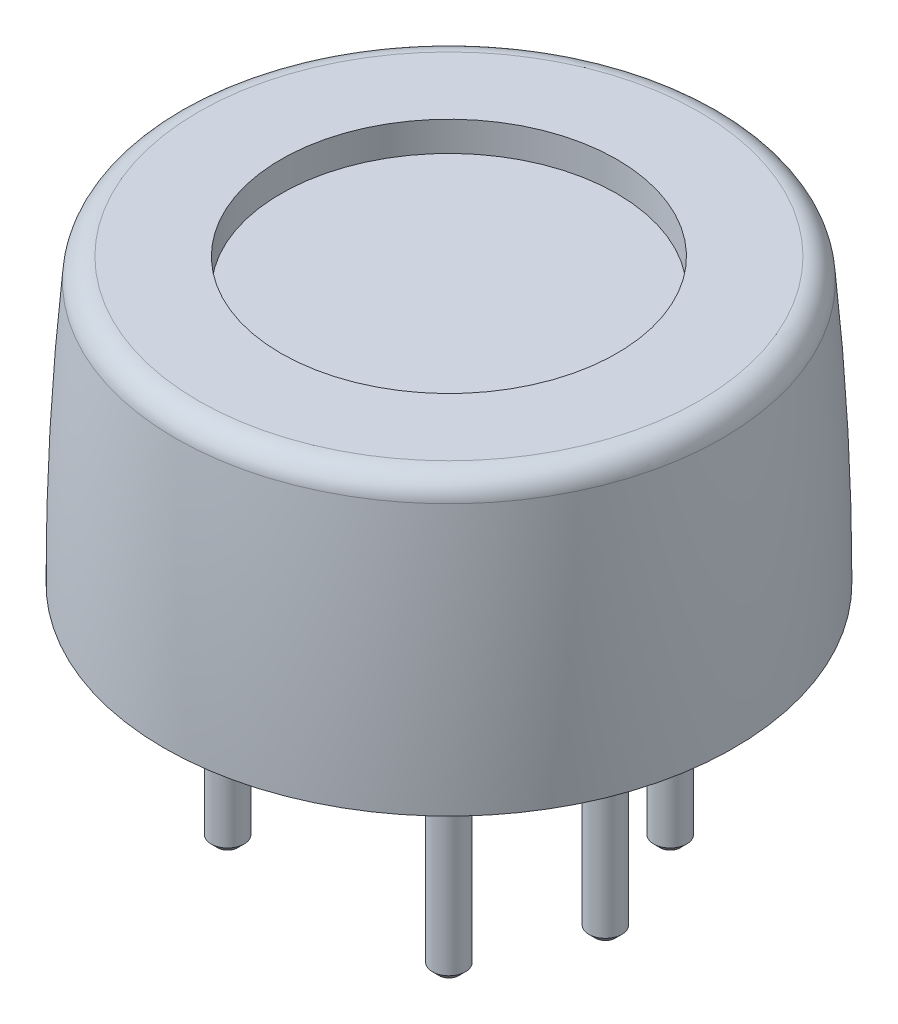
SolidWorks part; units mm, degrees
ref_plane "Спереди" through (0, 0, 0) normal (0, 0, 1) x (1, 0, 0)
ref_plane "Сверху" through (0, 0, 0) normal (0, 1, 0) x (1, 0, 0)
ref_plane "Справа" through (0, 0, 0) normal (1, 0, 0) x (0, 0, -1)
sketch "Эскиз1" plane through (0, 0, 0) normal (1, 0, 0) x (0, 0, -1)
  line L0 (0, 1.2) -> (-7.05, 1.2)
  line L1 (-7.05, 1.2) -> (-7.25, 1.4)
  line L2 (-7.25, 1.4) -> (-7.65, 1)
  line L3 (-7.65, 1) -> (-8.65, 1)
  line L4 (-7.6, 9.6) -> (-5.1, 9.6)
  line L5 (-5.1, 9.6) -> (-5.1, 8.7)
  line L6 (-5.1, 8.7) -> (0, 8.7)
  line L7 (0, 8.7) -> (0, 1.2)
  line L8 (0, 0) -> (0, 1.2) construction
  line L9 (-8.65, 1) -> (-8.65, 9.6) construction
  arc A0 (-8.65, 1) -> (-8.2973, 8.9619) centre (81.3821, 1) cw
  arc A1 (-8.2973, 8.9619) -> (-7.6, 9.6) centre (-7.6, 8.9) cw
  point P11 (6.5394, 0.6991)
  point P13 (-6.7788, 1.4697)
  point P14 (0, 0)
  point P16 (0, 0)
  point P17 (-7.25, 1.4173)
  point P18 (-7.25, 1.2964)
  point P19 (-7.65, 1.3579)
  point P20 (-8.0477, 0.7572)
  point P21 (-7.3516, 9.2373)
  point P22 (-8.2477, 0.6772)
  point P23 (-8.0343, 0.7197)
  point P24 (-7.9265, 0.7368)
  point P25 (-7.9051, 1)
  point P26 (-7.5397, 1)
  point P27 (-8.0561, 9.6)
  point P30 (-8.65, 9.6)
  dimension "D1" = 5.1
  dimension "D10" = 0.7
  dimension "D2" = 8.65
  dimension "D3" = 8.6
  dimension "D4" = 0.9
  dimension "D5" = 0.2
  dimension "D6" = 135
  dimension "D7" = 1.4
  dimension "D8" = 1.2
  dimension "D9" = 1
  dimension "D11" = 7.6
revolve "Повернуть1" add sketch "Эскиз1" angle 360 about L7
sketch "Эскиз2" plane through (0, 1.2, 0) normal (0, -1, 0) x (1, 0, 0)
  line L0 (-4.3841, 4.3841) -> (4.3841, -4.3841) construction
  line L2 (4.3841, 4.3841) -> (-4.3841, -4.3841) construction
  line L3 (0, 0) -> (0, 6.2) construction
  circle A0 centre (0, 0) radius 6.2
  circle A1 centre (0, 0) radius 3.35
  arc A2 (-3.3764, -3.3764) -> (-3.3764, 3.3764) centre (0, 0) cw construction
  arc A3 (3.3764, -3.3764) -> (3.3764, 3.3764) centre (0, 0) ccw construction
  arc A4 (-4.3841, 4.3841) -> (-2.3688, 2.3688) centre (-3.3764, 3.3764) cw
  arc A5 (-4.3841, -4.3841) -> (-2.3688, -2.3688) centre (-3.3764, -3.3764) ccw
  arc A6 (4.3841, 4.3841) -> (2.3688, 2.3688) centre (3.3764, 3.3764) ccw
  arc A7 (4.3841, -4.3841) -> (2.3688, -2.3688) centre (3.3764, -3.3764) cw
  point P6 (0, 0)
  point P10 (0, 0)
  point P19 (0, 0)
  point P20 (-2.2441, -2.2441)
  point P21 (-2.3333, 2.3333)
  point P22 (2.3875, 2.3875)
  dimension "D1" = 45
  dimension "D2" = 12.4
  dimension "D3" = 6.7
extrude "Бобышка-Вытянуть1" add sketch "Эскиз2" along normal blind 1.2 contours A0 A5 A1 A4 | A7 A0 A6 A1
sketch "Эскиз3" plane through (0, 0, 0) normal (0, -1, 0) x (1, 0, 0)
  line L0 (0, 0) -> (-6.2, 0) construction
  line L1 (-3.3588, 3.3588) -> (0, 0) construction
  line L2 (-3.3588, -3.3588) -> (0, 0) construction
  line L3 (0, 0) -> (0, -7.05) construction
  arc A0 (-4.3841, 4.3841) -> (-4.3841, -4.3841) centre (0, 0) ccw construction
  arc A1 (-2.2149, -4.202) -> (-2.2149, 4.202) centre (0, 0) cw construction
  arc A4 (-4.3841, -4.3841) -> (-2.3688, -2.3688) centre (-3.3764, -3.3764) ccw construction
  arc A5 (-2.3688, 2.3688) -> (-4.3841, 4.3841) centre (-3.3764, 3.3764) ccw construction
  circle A6 centre (-4.75, 0) radius 0.5
  circle A7 centre (-3.3588, 3.3588) radius 0.5
  circle A8 centre (-3.3588, -3.3588) radius 0.5
  circle A9 centre (0, 0) radius 7.05 construction
  circle A10 centre (3.3588, 3.3588) radius 0.5
  circle A11 centre (4.75, 0) radius 0.5
  circle A12 centre (3.3588, -3.3588) radius 0.5
  dimension "D1" = 4.75
  dimension "D2" = 45
  dimension "D3" = 1
  dimension "D4" = 45
extrude "Бобышка-Вытянуть2" add sketch "Эскиз3" along normal blind 5.8
chamfer "Фаска1" distance 0.2 angle 45 6 edges at (3.3588, -5.8, 3.8588) (4.75, -5.8, 0.5) (3.3588, -5.8, -2.8588) (-3.3588, -5.8, -3.8588) (-4.75, -5.8, -0.5) (-3.3588, -5.8, 2.8588)
